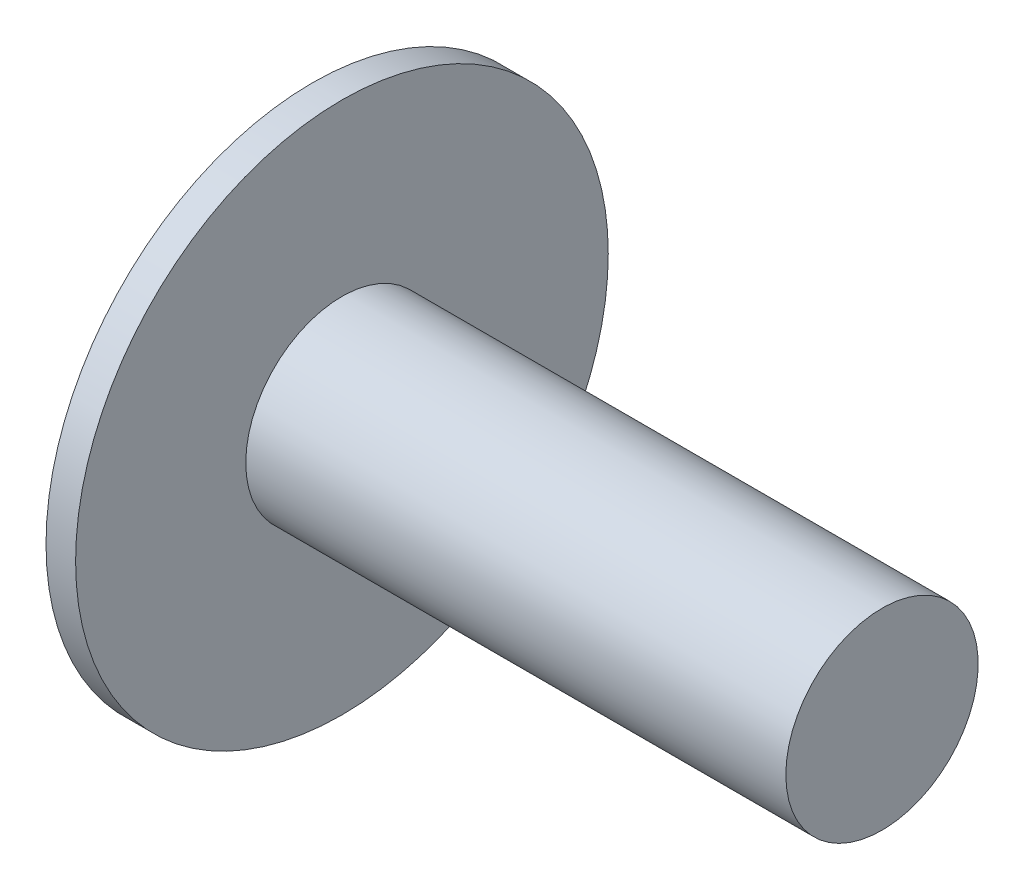
SolidWorks part; units mm, degrees
ref_plane "Front Plane" through (0, 0, 0) normal (0, 0, 1) x (1, 0, 0)
ref_plane "Top Plane" through (0, 0, 0) normal (0, 1, 0) x (1, 0, 0)
ref_plane "Right Plane" through (0, 0, 0) normal (1, 0, 0) x (0, 0, -1)
sketch "Sketch1" plane through (0, 0, 0) normal (0, 0, 1) x (1, 0, 0)
  line L0 (-29.6613, 0) -> (29.6613, 0) construction
  line L1 (0, 6.5) -> (36.5, 6.5)
  line L2 (0, 6.5) -> (0, 18)
  line L3 (0, 18) -> (-2, 18)
  line L4 (-2, 18) -> (-2, 0)
  line L5 (-2, 0) -> (36.5, 0)
  line L6 (36.5, 0) -> (36.5, 6.5)
  line L7 (-7.5539, 12.5) -> (7.6519, 12.5) construction
  dimension "D1" = 13
  dimension "D2" = 2
  dimension "D3" = 36.5
  dimension "D4" = 12.5
  dimension "D5" = 18
revolve "Revolve1" add sketch "Sketch1" angle 360 about L0
